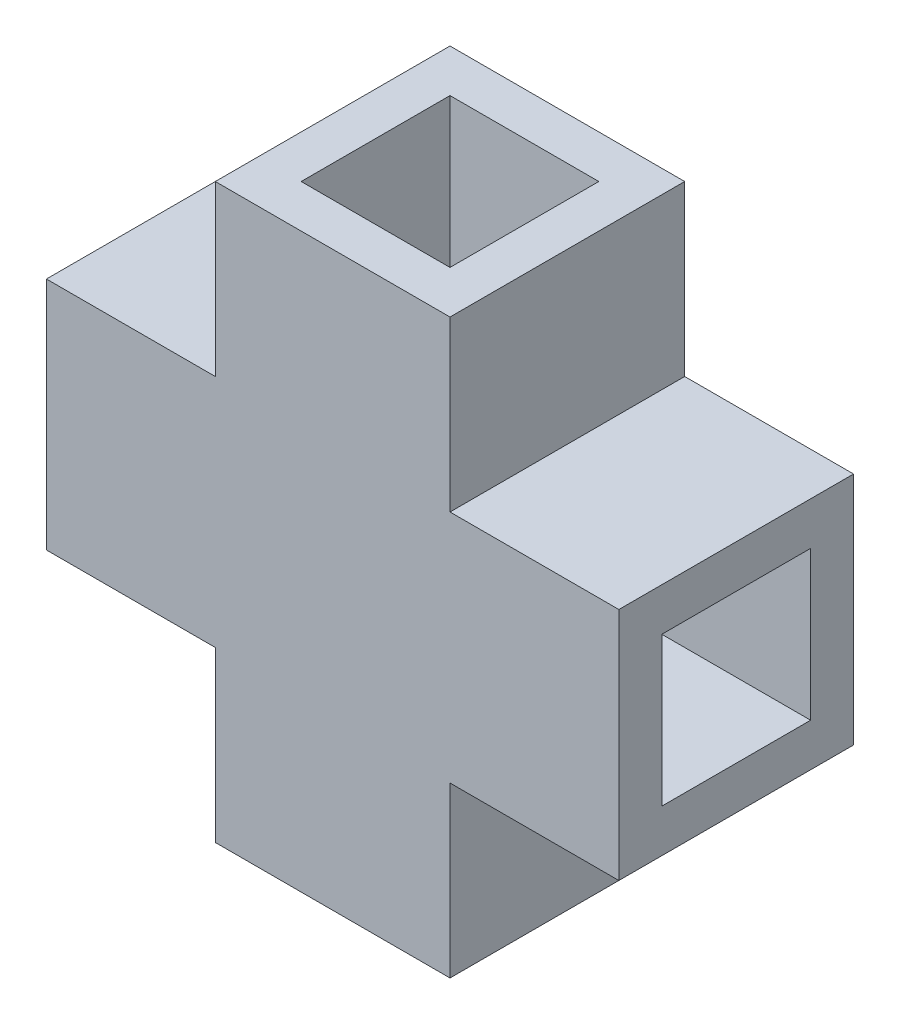
SolidWorks part; units mm, degrees
material "Ti-6Al-4VSolution treated and aged (SS)"
ref_plane "Front Plane" through (0, 0, 0) normal (0, 0, 1) x (1, 0, 0)
ref_plane "Top Plane" through (0, 0, 0) normal (0, 1, 0) x (1, 0, 0)
ref_plane "Right Plane" through (0, 0, 0) normal (1, 0, 0) x (0, 0, -1)
sketch "Sketch1" plane through (0, 0, 0) normal (0, 0, 1) x (1, 0, 0)
  line L0 (0, 10.9815) -> (0, -12.5751) construction
  line L1 (-19.1686, 0) -> (22.9792, 0) construction
  line L3 (-4.1, 10) -> (4.1, 10)
  line L4 (-4.1, 10) -> (-4.1, -10)
  line L5 (-4.1, -10) -> (4.1, -10)
  line L6 (4.1, 10) -> (4.1, -10)
  line L7 (-4.1, 10) -> (4.1, -10) construction
  line L8 (-4.1, -10) -> (4.1, 10) construction
  line L9 (-10, 4.1) -> (10, 4.1)
  line L10 (-10, 4.1) -> (-10, -4.1)
  line L11 (-10, -4.1) -> (10, -4.1)
  line L12 (10, 4.1) -> (10, -4.1)
  line L13 (-10, 4.1) -> (10, -4.1) construction
  line L14 (-10, -4.1) -> (10, 4.1) construction
  point P5 (0, 0)
  point P10 (0, 0)
  dimension "D1" = 20
  dimension "D2" = 8.2
extrude "Boss-Extrude1" add sketch "Sketch1" along normal blind 8.2 contours L10 L11 L4 L9 | L4 L9 L6 L3 | L4 L11 L6 L9 | L12 L9 L6 L11 | L11 L4 L5 L6
shell "Shell1" thickness 1.5
